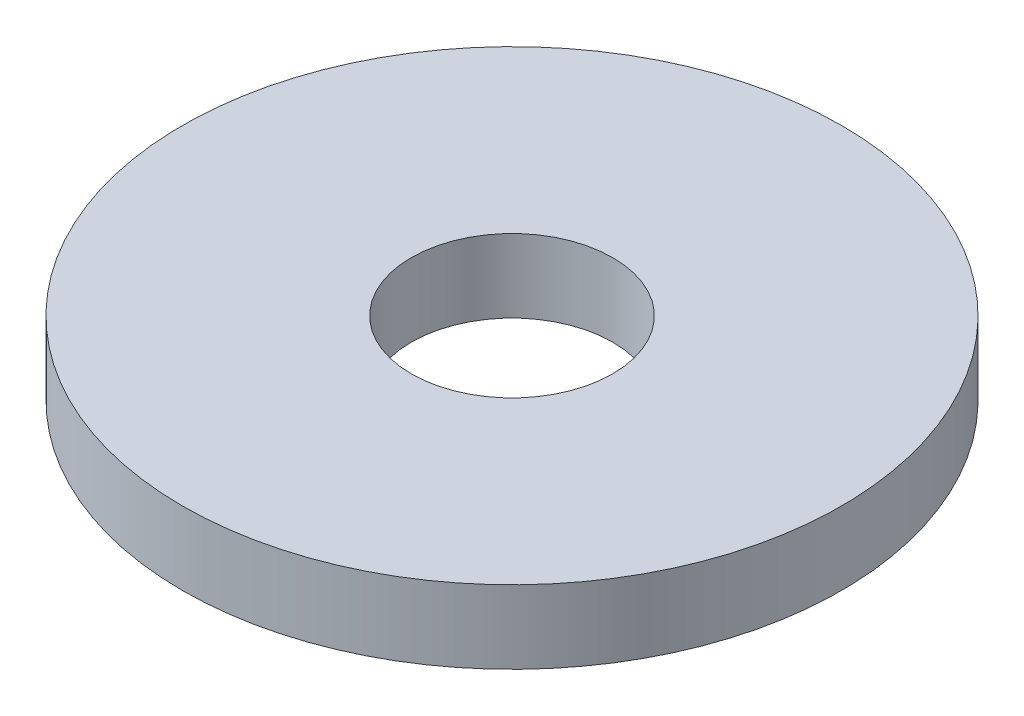
SolidWorks part; units mm, degrees
material "AISI 1035 Stahl"
ref_plane "Plane1" through (0, 0, 0) normal (0, 0, 1) x (1, 0, 0)
ref_plane "Plane2" through (0, 0, 0) normal (0, 1, 0) x (1, 0, 0)
ref_plane "Plane3" through (0, 0, 0) normal (1, 0, 0) x (0, 0, -1)
sketch "Sketch1" plane through (0, 0, 0) normal (0, 1, 0) x (1, 0, 0)
  circle A0 centre (0, 0) radius 9
  dimension "OutsideDia" = 18
extrude "Base-Extrude" add sketch "Sketch1" against normal blind 2
sketch "Sketch2" plane through (0, 0, 0) normal (0, 1, 0) x (-1, 0, 0)
  circle A0 centre (0, 0) radius 2.75
  dimension "HoleDia" = 5.5
extrude "Type-R" cut sketch "Sketch2" against normal through all
sketch "Sketch3" plane through (0, 0, 0) normal (0, 1, 0) x (-1, 0, 0)
  line L1 (2.75, 2.75) -> (-2.75, 2.75)
  line L2 (2.75, 2.75) -> (2.75, -2.75)
  line L3 (2.75, -2.75) -> (-2.75, -2.75)
  line L4 (-2.75, 2.75) -> (-2.75, -2.75)
  dimension "SquareSize" = 5.5
  dimension "D1" = 5.5
  dimension "D2" = 2.75
  dimension "D3" = 2.75
extrude "Type-V" [suppressed] cut sketch "Sketch3" against normal through all
equation "\"D1@Sketch3\" = \"SquareSize@Sketch3\""
equation "\"D2@Sketch3\" = \"SquareSize@Sketch3\" / 2"
equation "\"D3@Sketch3\" = \"D1@Sketch3\" / 2"
